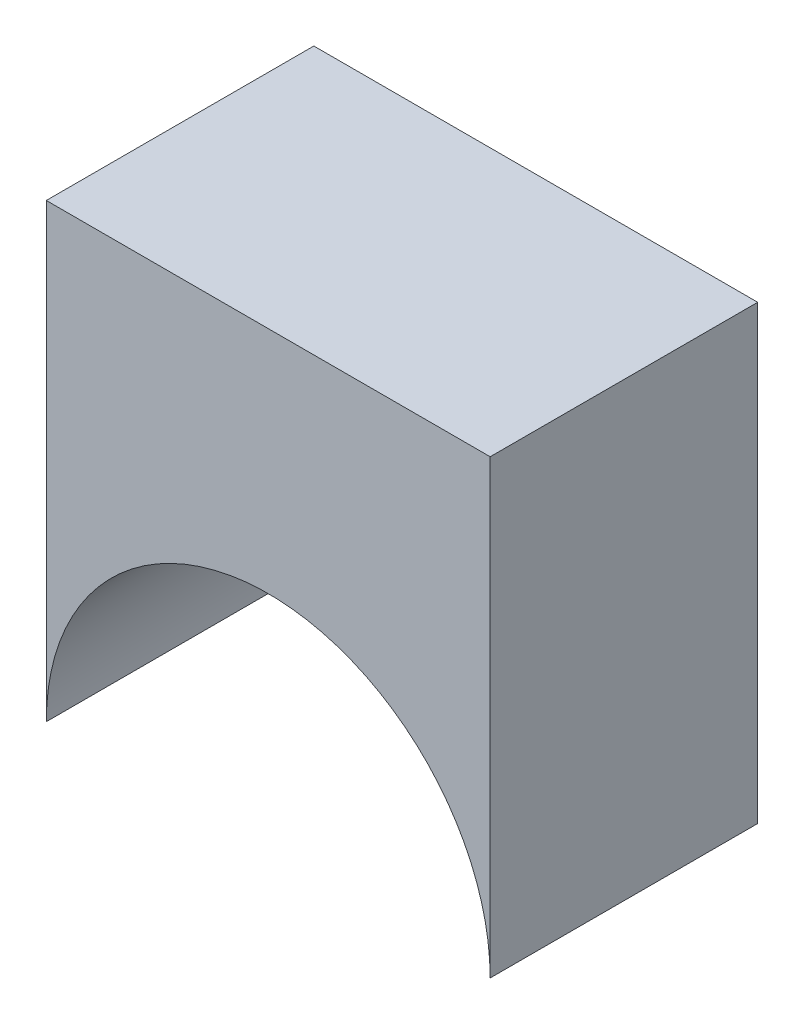
SolidWorks part; units mm, degrees
ref_plane "Front Plane" through (0, 0, 0) normal (0, 0, 1) x (1, 0, 0)
ref_plane "Top Plane" through (0, 0, 0) normal (0, 1, 0) x (1, 0, 0)
ref_plane "Right Plane" through (0, 0, 0) normal (1, 0, 0) x (0, 0, -1)
sketch "Sketch1" plane through (0, 0, 0) normal (0, 1, 0) x (1, 0, 0)
  line L1 (-18.5, 11.15) -> (18.5, 11.15)
  line L2 (-18.5, 11.15) -> (-18.5, -11.15)
  line L3 (-18.5, -11.15) -> (18.5, -11.15)
  line L4 (18.5, 11.15) -> (18.5, -11.15)
  line L5 (-18.5, 11.15) -> (18.5, -11.15) construction
  line L6 (-18.5, -11.15) -> (18.5, 11.15) construction
  point P0 (0, 0)
  dimension "D1" = 37
  dimension "D2" = 22.3
extrude "Boss-Extrude1" add sketch "Sketch1" along normal blind 19.13
ref_plane "Plane1" through (0, 0, 11.15) normal (0, 0, 1) x (1, 0, 0)
sketch "Sketch2" plane through (0, 0, 11.15) normal (0, 0, 1) x (1, 0, 0)
  line L0 (-18.5, 0) -> (-18.5, -18.5)
  line L1 (18.5, 0) -> (18.5, -18.5)
  line L2 (-18.5, 0) -> (18.5, 0)
  arc A0 (-18.5, -18.5) -> (18.5, -18.5) centre (0, -18.5) cw
  dimension "D1" = 18.5
extrude "Boss-Extrude2" add sketch "Sketch2" against normal blind 22.3 contours L0 A0 L2 | L2 A0 L1
